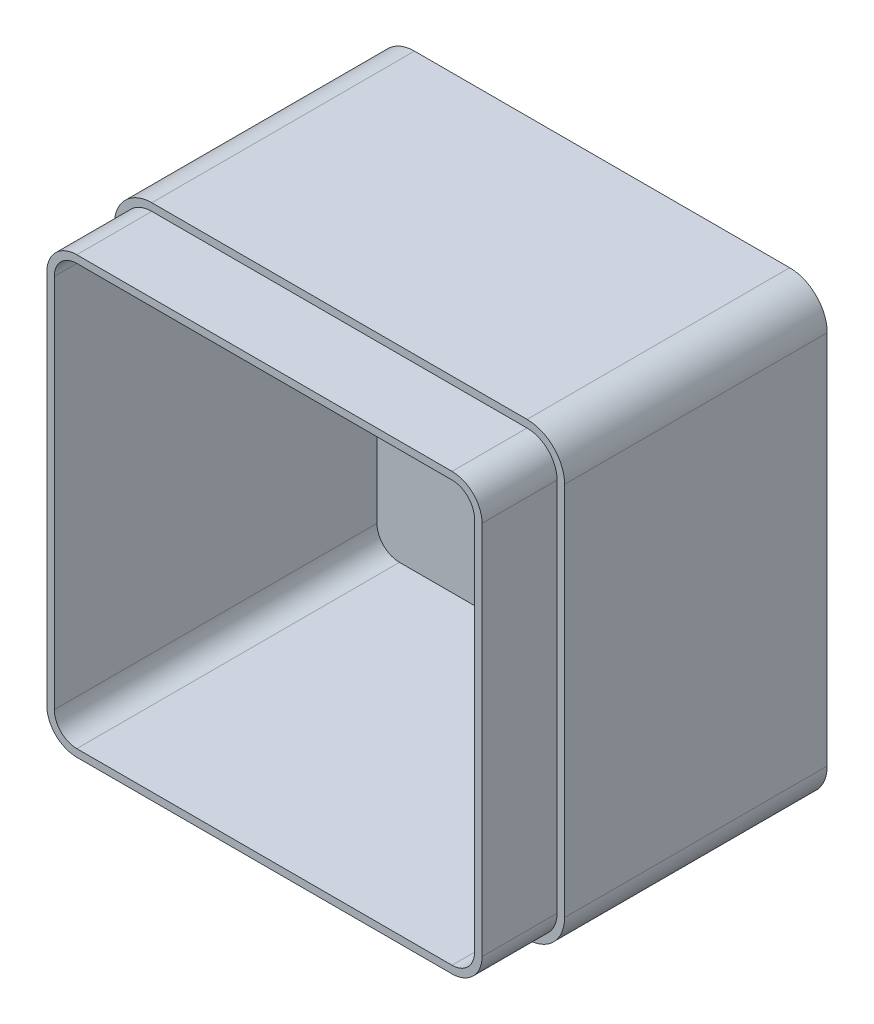
SolidWorks part; units mm, degrees
ref_plane "Front" through (0, 0, 0) normal (0, 0, 1) x (1, 0, 0)
ref_plane "Top" through (0, 0, 0) normal (0, 1, 0) x (1, 0, 0)
ref_plane "Right" through (0, 0, 0) normal (1, 0, 0) x (0, 0, -1)
sketch "Sketch1" plane through (0, 0, 0) normal (0, 0, 1) x (1, 0, 0)
  line L1 (0, 0) -> (120, 0)
  line L2 (0, 0) -> (0, 120)
  line L3 (0, 120) -> (120, 120)
  line L4 (120, 0) -> (120, 120)
  dimension "D1" = 120
  dimension "D2" = 120
extrude "Boss-Extrude1" add sketch "Sketch1" along normal blind 90
fillet "Fillet1" radius 10 4 edges at (120, 120, 45) (120, 0, 45) (0, 0, 45) (0, 120, 45)
shell "Shell1" thickness 4
sketch "Sketch2" plane through (0, 0, 90) normal (0, 0, 1) x (1, 0, 0)
  line L4 (120, 10) -> (120, 110)
  line L5 (110, 120) -> (10, 120)
  line L6 (0, 110) -> (0, 10)
  line L7 (10, 0) -> (110, 0)
  line L8 (120, 10) -> (120, 110)
  line L9 (110, 120) -> (10, 120)
  line L10 (0, 110) -> (0, 10)
  line L11 (10, 0) -> (110, 0)
  line L16 (118, 10) -> (118, 110)
  line L17 (110, 118) -> (10, 118)
  line L18 (2, 110) -> (2, 10)
  line L19 (10, 2) -> (110, 2)
  line L20 (118, 10) -> (118, 110)
  line L21 (110, 118) -> (10, 118)
  line L22 (2, 110) -> (2, 10)
  line L23 (10, 2) -> (110, 2)
  arc A4 (120, 110) -> (110, 120) centre (110, 110) ccw
  arc A5 (10, 120) -> (0, 110) centre (10, 110) ccw
  arc A6 (0, 10) -> (10, 0) centre (10, 10) ccw
  arc A7 (110, 0) -> (120, 10) centre (110, 10) ccw
  arc A8 (120, 110) -> (110, 120) centre (110, 110) ccw
  arc A9 (10, 120) -> (0, 110) centre (10, 110) ccw
  arc A10 (0, 10) -> (10, 0) centre (10, 10) ccw
  arc A11 (110, 0) -> (120, 10) centre (110, 10) ccw
  arc A16 (118, 110) -> (110, 118) centre (110, 110) ccw
  arc A17 (10, 118) -> (2, 110) centre (10, 110) ccw
  arc A18 (2, 10) -> (10, 2) centre (10, 10) ccw
  arc A19 (110, 2) -> (118, 10) centre (110, 10) ccw
  arc A20 (118, 110) -> (110, 118) centre (110, 110) ccw
  arc A21 (10, 118) -> (2, 110) centre (10, 110) ccw
  arc A22 (2, 10) -> (10, 2) centre (10, 10) ccw
  arc A23 (110, 2) -> (118, 10) centre (110, 10) ccw
  dimension "D1" = 0
  dimension "D2" = 2
extrude "Cut-Extrude1" cut sketch "Sketch2" against normal blind 20
